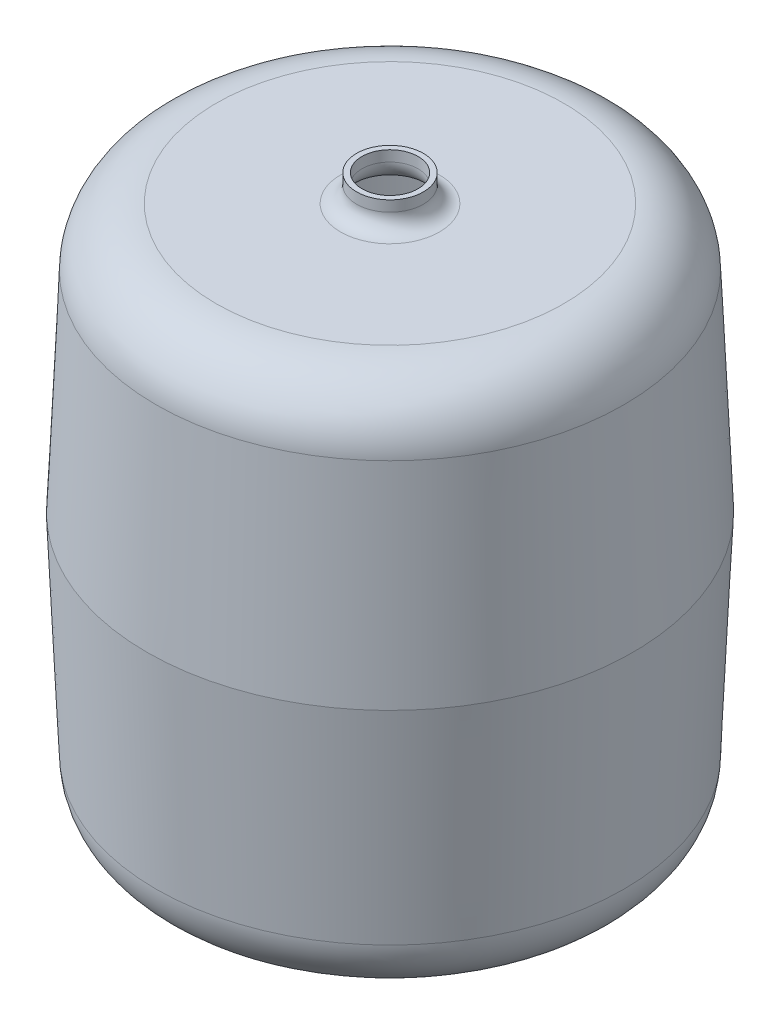
SolidWorks part; units mm, degrees
material "1060 Alloy"
ref_plane "Front Plane" through (0, 0, 0) normal (0, 0, 1) x (1, 0, 0)
ref_plane "Top Plane" through (0, 0, 0) normal (0, 1, 0) x (1, 0, 0)
ref_plane "Right Plane" through (0, 0, 0) normal (1, 0, 0) x (0, 0, -1)
sketch "Sketch1" plane through (0, 0, 0) normal (0, 0, 1) x (1, 0, 0)
  line L0 (0, 434.4122) -> (0, 0) construction
  line L1 (0, 0) -> (130.0428, 0)
  line L2 (175, 43.0371) -> (181.8531, 200)
  line L3 (181.8531, 200) -> (175, 356.9629)
  line L4 (130.0428, 400) -> (37, 400)
  line L5 (-50.5775, 200) -> (321.1421, 200) construction
  line L6 (25, 412) -> (25, 420)
  line L7 (0, 4) -> (130.0428, 4)
  line L8 (171.0038, 43.2116) -> (177.8493, 200)
  line L9 (177.8493, 200) -> (171.0038, 356.7884)
  line L10 (130.0428, 396) -> (37, 396)
  line L11 (21, 412) -> (21, 420)
  line L12 (21, 420) -> (25, 420)
  line L13 (0, 4) -> (0, 0)
  arc A0 (130.0428, 0) -> (175, 43.0371) centre (130.0428, 45) ccw
  arc A1 (175, 356.9629) -> (130.0428, 400) centre (130.0428, 355) ccw
  arc A2 (37, 400) -> (25, 412) centre (37, 412) cw
  arc A3 (130.0428, 4) -> (171.0038, 43.2116) centre (130.0428, 45) ccw
  arc A4 (171.0038, 356.7884) -> (130.0428, 396) centre (130.0428, 355) ccw
  arc A5 (37, 396) -> (21, 412) centre (37, 412) cw
  dimension "D2" = 92.5
  dimension "D5" = 45
  dimension "D6" = 45
  dimension "D8" = 25
  dimension "D9" = 12
  dimension "D3" = 400
  dimension "D4" = 175
  dimension "D7" = 200
  dimension "D10" = 20
  dimension "D12" = 92.5
  dimension "D11" = 4
revolve "Revolve1" add sketch "Sketch1" angle 360 about L0
equation "\"A\"= 350"
equation "\"B\"= 400"
